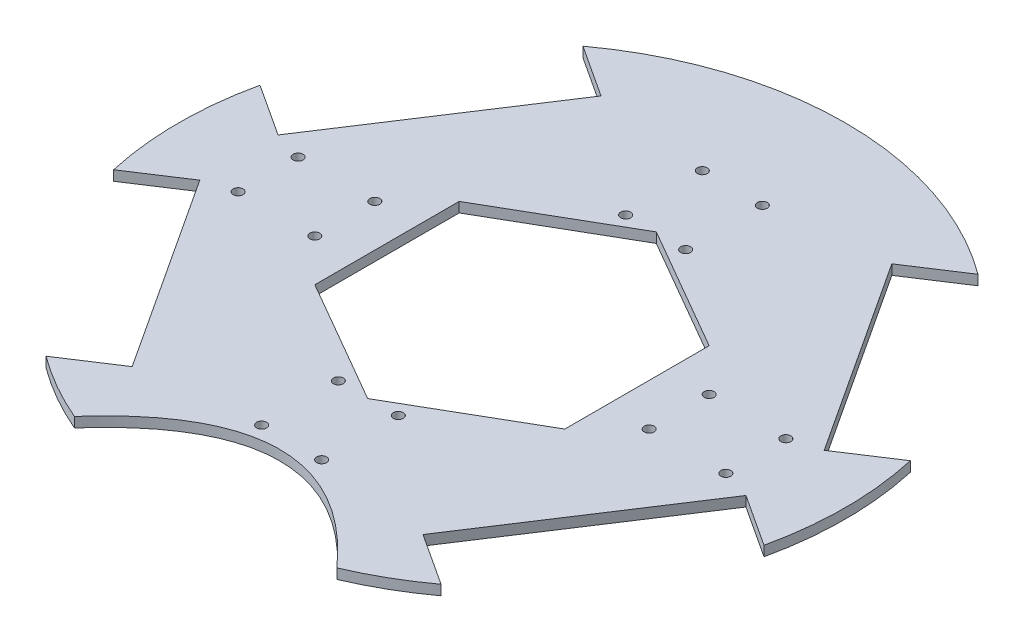
SolidWorks part; units mm, degrees
ref_plane "Front Plane" through (0, 0, 0) normal (0, 0, 1) x (1, 0, 0)
ref_plane "Top Plane" through (0, 0, 0) normal (0, 1, 0) x (1, 0, 0)
ref_plane "Right Plane" through (0, 0, 0) normal (1, 0, 0) x (0, 0, -1)
sketch "Sketch2" plane through (0, 0, 0) normal (0, 1, 0) x (1, 0, 0)
  line L0 (-39.3568, -91.9296) -> (39.3568, -91.9296)
  line L1 (0, -91.9296) -> (0, -69.6892)
  circle A0 centre (0, 0) radius 100
  spline S0 degree 2 poles (-39.3568, -91.9296) (0, -47.4489) (39.3568, -91.9296) knots 0 0 0 1 1 1
extrude "Boss-Extrude1" add sketch "Sketch2" along normal blind 3 contours A0 S0
sketch "Sketch3" plane through (0, 3, 0) normal (0, 1, 0) x (1, 0, 0)
  line L1 (-83.7038, -54.7145) -> (-64.5537, -84.0108)
  line L2 (-64.5537, -84.0108) -> (-43.6277, -70.3322)
  line L3 (-83.7038, -54.7145) -> (-102.8539, -25.4182)
  line L4 (-102.8539, -25.4182) -> (-81.9279, -11.7396)
  line L5 (-81.9279, -11.7396) -> (-43.6277, -70.3322)
  line L6 (83.7038, 54.7145) -> (64.5537, 84.0108)
  line L7 (64.5537, 84.0108) -> (102.8539, 25.4182)
  line L8 (102.8539, 25.4182) -> (81.9279, 11.7396)
  line L9 (81.9279, 11.7396) -> (43.6277, 70.3322)
  line L10 (43.6277, 70.3322) -> (64.5537, 84.0108)
  line L13 (-83.7038, 54.7145) -> (-102.8539, 25.4182)
  line L14 (-102.8539, 25.4182) -> (-81.9279, 11.7396)
  line L15 (-81.9279, 11.7396) -> (-43.6277, 70.3322)
  line L16 (-43.6277, 70.3322) -> (-64.5537, 84.0108)
  line L17 (-64.5537, 84.0108) -> (-83.7038, 54.7145)
  line L18 (83.7038, -54.7145) -> (64.5537, -84.0108)
  line L19 (64.5537, -84.0108) -> (102.8539, -25.4182)
  line L20 (102.8539, -25.4182) -> (81.9279, -11.7396)
  line L21 (81.9279, -11.7396) -> (43.6277, -70.3322)
  line L22 (43.6277, -70.3322) -> (64.5537, -84.0108)
  arc A0 (39.3568, -91.9296) -> (-39.3568, -91.9296) centre (0, 0) ccw construction
  arc M10 (39.3568, -91.9296) -> (-39.3568, -91.9296) centre (0, 0) ccw
extrude "Cut-Extrude1" cut sketch "Sketch3" against normal blind 3 contours L15 L16 L14 M10 | L10 L9 L8 M10 | L21 L22 L20 M10 | L5 L4 L2 M10
sketch "Sketch4" plane through (0, 3, 0) normal (0, 1, 0) x (1, 0, 0)
  line L1 (0, 43.3013) -> (-37.5, 21.6506)
  line L2 (-37.5, 21.6506) -> (-37.5, -21.6506)
  line L3 (-37.5, -21.6506) -> (0, -43.3013)
  line L4 (0, -43.3013) -> (37.5, -21.6506)
  line L5 (37.5, -21.6506) -> (37.5, 21.6506)
  line L6 (37.5, 21.6506) -> (0, 43.3013)
  circle A0 centre (0, 0) radius 37.5 construction
extrude "Cut-Extrude2" cut sketch "Sketch4" against normal blind 3 contours L1 L2 L3 L4 L5 L6
sketch "Sketch5" plane through (0, 3, 0) normal (0, 1, 0) x (1, 0, 0)
  line L25 (-37.5, 21.6506) -> (-37.5, -21.6506) construction
  line L30 (-37.5, 9) -> (-37.5, -9)
  circle A0 centre (-73.1625, 9) radius 1.5
  circle A1 centre (-50.1625, 9) radius 1.5
  circle A2 centre (-50.1625, -9) radius 1.5
  circle A3 centre (-73.1625, -9) radius 1.5
  circle A4 centre (50.16, 9) radius 1.5
  circle A5 centre (50.16, -9) radius 1.5
  circle A6 centre (73.16, 9) radius 1.5
  circle A7 centre (73.16, -9) radius 1.5
  circle A8 centre (-9, -43.1051) radius 1.5
  circle A9 centre (9, -43.1051) radius 1.5
  circle A10 centre (-9, -66.1051) radius 1.5
  circle A11 centre (9, -66.1051) radius 1.5
  circle A12 centre (-9, 66.1051) radius 1.5
  circle A13 centre (9, 66.1051) radius 1.5
  circle A14 centre (-9, 43.1051) radius 1.5
  circle A15 centre (9, 43.1051) radius 1.5
extrude "Cut-Extrude4" cut sketch "Sketch5" against normal blind 3 contours A0 | A3 | A2 | A1 | A13 | A12 | A14 | A15 | A6 | A5 | A9 | A8 | A10 | A11 | A4 | A7
sketch "Sketch6" plane through (0, 3, 0) normal (0, 1, 0) x (1, 0, 0)
  line L0 (0, 0) -> (0, 55)
  line L7 (0, 0) -> (55, 0)
  line L8 (0, 0) -> (0, -55)
  line L9 (0, 0) -> (-55, 0)
  line L10 (-62.7778, -41.0359) -> (62.7778, -41.0359)
  line L11 (-81.9279, -11.7396) -> (-43.6277, -70.3322) construction
  line L12 (81.9279, -11.7396) -> (43.6277, -70.3322) construction
  line L13 (-73.1625, 9) -> (-50.1625, 9)
  line L14 (-50.1625, 9) -> (-50.1625, -9)
  dimension "D1" = 23
  dimension "D2" = 18
